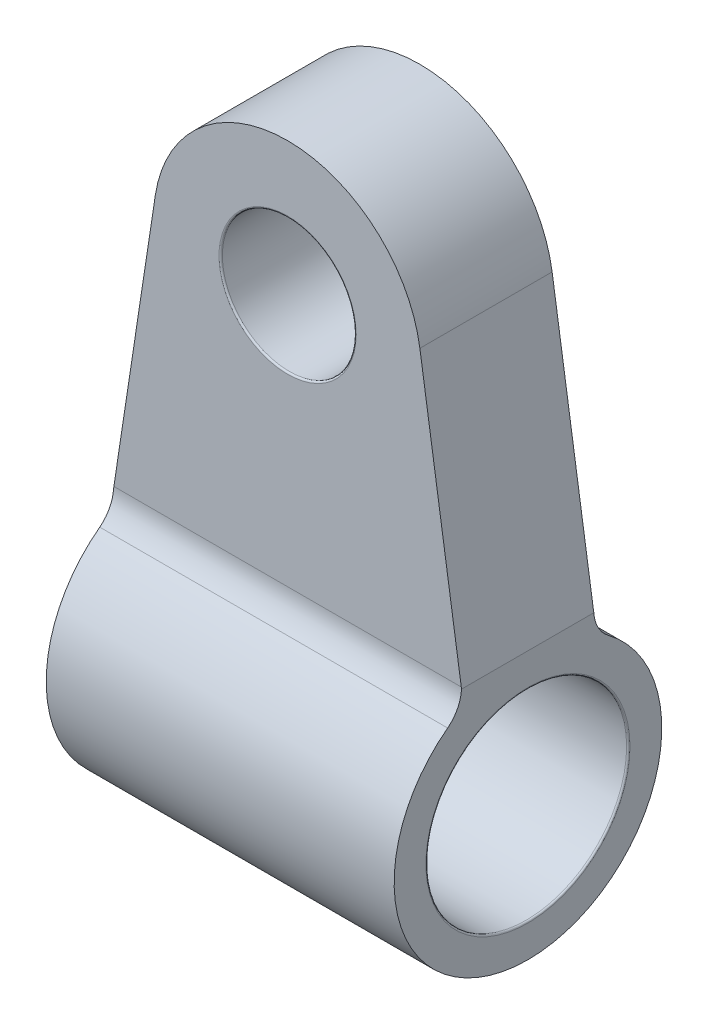
SolidWorks part; units mm, degrees
ref_plane "Front Plane" through (0, 0, 0) normal (0, 0, 1) x (1, 0, 0)
ref_plane "Top Plane" through (0, 0, 0) normal (0, 1, 0) x (1, 0, 0)
ref_plane "Right Plane" through (0, 0, 0) normal (1, 0, 0) x (0, 0, -1)
sketch "Sketch1" plane through (0, 0, 0) normal (1, 0, 0) x (0, 0, -1)
  circle A0 centre (0, 0) radius 20
  dimension "D1" = 40
extrude "Boss-Extrude1" add sketch "Sketch1" along normal mid plane 52
sketch "Sketch3" plane through (0, 0, 0) normal (0, 0, 1) x (1, 0, 0)
  line L0 (-26, 20) -> (-19.7733, 61.0028)
  line L1 (26, 20) -> (-26, 20) construction
  line L2 (0, 78) -> (0, 0) construction
  line L4 (-26, 20) -> (-26, 78)
  line L5 (-26, 78) -> (0, 78)
  arc A0 (-19.7733, 61.0028) -> (0, 78) centre (0, 58) cw
  dimension "D3" = 38
sketch "Sketch4" plane through (-26, 0, 0) normal (-1, 0, 0) x (0, 0, 1)
  line L0 (-12, 16) -> (12, 16) construction
  line L1 (-9.8393, 20.254) -> (-9.8393, 78)
  line L2 (-9.8393, 78) -> (9.9279, 78)
  line L3 (9.9279, 78) -> (9.9279, 20.254)
  line L4 (0, 20) -> (0, 78) construction
  line L5 (0, 61.0028) -> (0, 78) construction
  arc A0 (-12, 16) -> (12, 16) centre (0, 0) cw
  circle A1 centre (0, 0) radius 20 construction
  arc A2 (-12, 16) -> (-9.8393, 20.254) centre (-15.2416, 20.3222) ccw
  arc A3 (9.9279, 20.254) -> (12, 16) centre (15.3306, 20.254) ccw
  dimension "D1" = 24
  dimension "D2" = 58
extrude "Boss-Extrude2" add sketch "Sketch4" against normal blind 52
extrude "Cut-Extrude2" cut sketch "Sketch3" against normal mid plane 52
mirror "Mirror1" about plane through (0, 0, 0) normal (1, 0, 0) of "Cut-Extrude2"
sketch "Sketch7" plane through (0, 0, 9.9279) normal (0, 0, 1) x (1, 0, 0)
  circle A0 centre (0, 58) radius 10
  arc A3 (19.7733, 61.0028) -> (-19.7733, 61.0028) centre (0, 58) ccw construction
  point P2 (0, 78)
  dimension "D1" = 20
  dimension "D2" = 20
extrude "Cut-Extrude3" cut sketch "Sketch7" against normal blind 52
sketch "Sketch8" plane through (26, 0, 0) normal (1, 0, 0) x (0, 0, -1)
  circle A0 centre (0, 0) radius 15
  dimension "D1" = 30
extrude "Cut-Extrude4" cut sketch "Sketch8" against normal blind 52
fillet "Fillet1" radius 0.25 4 edges at (0, 68, -9.8393) (-26, 0, -15) (26, 0, -15) (10, 58, 9.9279)
